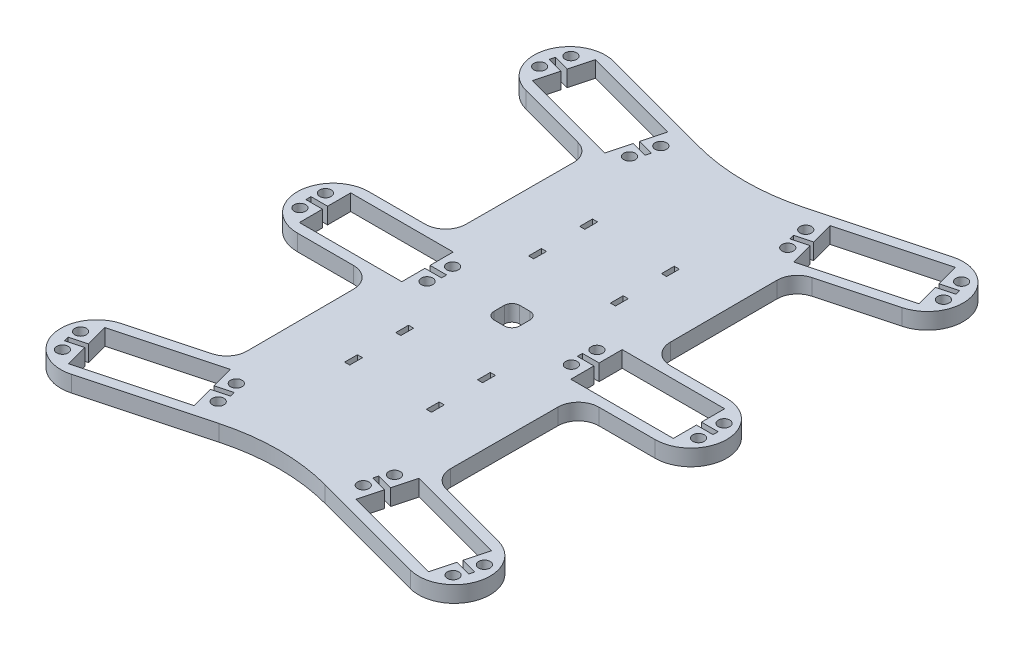
SolidWorks part; units mm, degrees
ref_plane "Front Plane" through (0, 0, 0) normal (0, 0, 1) x (1, 0, 0)
ref_plane "Top Plane" through (0, 0, 0) normal (0, 1, 0) x (1, 0, 0)
ref_plane "Right Plane" through (0, 0, 0) normal (1, 0, 0) x (0, 0, -1)
sketch "Sketch1" plane through (0, 0, 0) normal (0, 1, 0) x (1, 0, 0)
  line L0 (0, 32.1883) -> (0, -21.4181) construction
  line L1 (0, 0) -> (27.1703, 0) construction
  line L2 (-70, 14) -> (-40, 14)
  line L3 (-40, 14) -> (-39.8161, 70)
  line L4 (-39.8161, 70) -> (-73.6235, 79.0587)
  line L5 (-66.3765, 106.1046) -> (0, 88.3191)
  line L10 (-66.3765, 106.1046) -> (-73.6235, 79.0587) construction
  line L12 (-70, 14) -> (-70, -14) construction
  line L14 (-66.3765, -106.1046) -> (0, -88.3191)
  line L15 (-39.8161, -70) -> (-73.6235, -79.0587)
  line L16 (-40, -14) -> (-39.8161, -70)
  line L17 (-70, -14) -> (-40, -14)
  line L18 (66.3765, -106.1046) -> (0, -88.3191)
  line L19 (66.3765, 106.1046) -> (0, 88.3191)
  line L20 (70, 14) -> (70, -14) construction
  line L21 (66.3765, 106.1046) -> (73.6235, 79.0587) construction
  line L22 (70, -14) -> (40, -14)
  line L23 (40, -14) -> (39.8161, -70)
  line L24 (39.8161, -70) -> (73.6235, -79.0587)
  line L25 (39.8161, 70) -> (73.6235, 79.0587)
  line L26 (40, 14) -> (39.8161, 70)
  line L27 (70, 14) -> (40, 14)
  line L28 (-70.4609, 103.1096) -> (-75.6631, 83.6945)
  line L29 (-75.6631, 83.6945) -> (-36.9295, 73.3159)
  line L30 (-36.9295, 73.3159) -> (-31.7272, 92.731)
  line L31 (-31.7272, 92.731) -> (-70.4609, 103.1096)
  line L32 (-51.094, 97.9203) -> (-56.2963, 78.5052) construction
  line L33 (-70, 92.5816) -> (-73.062, 93.4021) construction
  line L34 (-53.12, 10.05) -> (-53.12, -10.05) construction
  line L35 (-73.17, 10.05) -> (-33.07, 10.05)
  line L36 (-73.17, 10.05) -> (-73.17, -10.05)
  line L37 (-73.17, -10.05) -> (-33.07, -10.05)
  line L38 (-33.07, 10.05) -> (-33.07, -10.05)
  line L39 (-73.17, 10.05) -> (-33.07, -10.05) construction
  line L40 (-73.17, -10.05) -> (-33.07, 10.05) construction
  line L41 (-36.9295, -73.3159) -> (-31.7272, -92.731)
  line L42 (-31.7272, -92.731) -> (-70.4609, -103.1096)
  line L43 (-70.4609, -103.1096) -> (-75.6631, -83.6945)
  line L44 (-75.6631, -83.6945) -> (-36.9295, -73.3159)
  line L45 (36.9295, 73.3159) -> (31.7272, 92.731)
  line L46 (75.6631, 83.6945) -> (36.9295, 73.3159)
  line L47 (70.4609, 103.1096) -> (75.6631, 83.6945)
  line L48 (31.7272, 92.731) -> (70.4609, 103.1096)
  line L49 (73.17, -10.05) -> (33.07, 10.05) construction
  line L50 (73.17, 10.05) -> (33.07, -10.05) construction
  line L51 (53.12, 10.05) -> (53.12, -10.05) construction
  line L52 (33.07, 10.05) -> (33.07, -10.05)
  line L53 (73.17, -10.05) -> (33.07, -10.05)
  line L54 (73.17, 10.05) -> (73.17, -10.05)
  line L55 (73.17, 10.05) -> (33.07, 10.05)
  line L56 (36.9295, -73.3159) -> (31.7272, -92.731)
  line L57 (75.6631, -83.6945) -> (36.9295, -73.3159)
  line L58 (31.7272, -92.731) -> (70.4609, -103.1096)
  line L59 (70.4609, -103.1096) -> (75.6631, -83.6945)
  line L60 (-76.4333, 99.4818) -> (-79.0215, 89.8226) construction
  line L61 (-77.7274, 94.6522) -> (-70, 92.5816) construction
  line L62 (-78, 5) -> (-78, -5) construction
  arc A0 (-70, 14) -> (-70, -14) centre (-70, 0) ccw
  arc A1 (-66.3765, 106.1046) -> (-73.6235, 79.0587) centre (-70, 92.5816) ccw
  circle A8 centre (-76.4333, 99.4818) radius 2.25
  circle A9 centre (-79.0215, 89.8226) radius 2.25
  circle A10 centre (-78, 5) radius 2.25
  arc A11 (-66.3765, -106.1046) -> (-73.6235, -79.0587) centre (-70, -92.5816) cw
  circle A12 centre (-79.0215, -89.8226) radius 2.25
  circle A13 centre (-76.4333, -99.4818) radius 2.25
  circle A14 centre (-78, -5) radius 2.25
  circle A15 centre (78, -5) radius 2.25
  circle A16 centre (76.4333, -99.4818) radius 2.25
  circle A17 centre (79.0215, -89.8226) radius 2.25
  arc A18 (66.3765, -106.1046) -> (73.6235, -79.0587) centre (70, -92.5816) ccw
  circle A19 centre (78, 5) radius 2.25
  circle A20 centre (79.0215, 89.8226) radius 2.25
  circle A21 centre (76.4333, 99.4818) radius 2.25
  arc A22 (66.3765, 106.1046) -> (73.6235, 79.0587) centre (70, 92.5816) cw
  arc A23 (70, 14) -> (70, -14) centre (70, 0) cw
  circle A24 centre (-30.957, 76.9437) radius 2.25
  circle A25 centre (-28.3688, 86.603) radius 2.25
  circle A26 centre (-28.24, -5) radius 2.25
  circle A27 centre (-28.24, 5) radius 2.25
  circle A28 centre (-28.3688, -86.603) radius 2.25
  circle A29 centre (-30.957, -76.9437) radius 2.25
  circle A30 centre (28.3688, 86.603) radius 2.25
  circle A31 centre (30.957, 76.9437) radius 2.25
  circle A32 centre (28.24, 5) radius 2.25
  circle A33 centre (28.24, -5) radius 2.25
  circle A34 centre (30.957, -76.9437) radius 2.25
  circle A35 centre (28.3688, -86.603) radius 2.25
  point P60 (-51.094, 97.9203)
  point P62 (-56.2963, 78.5052)
  point P65 (-73.062, 93.4021)
  point P71 (-53.12, 0)
  point P108 (53.12, 0)
  point P118 (-83.523, 96.2051)
  dimension "D2" = 14
  dimension "D3" = 10
  dimension "D8" = 4.5
  dimension "D1" = 75
  dimension "D4" = 70
  dimension "D5" = 30
  dimension "D6" = 35
  dimension "D7" = 56
  dimension "D9" = 8
  dimension "D10" = 5
  dimension "D11" = 10
  dimension "D12" = 40.1
  dimension "D13" = 20.1
  dimension "D14" = 4.83
  dimension "D15" = 40.1
  dimension "D16" = 20.1
  dimension "D17" = 4.83
  dimension "D18" = 8
extrude "Boss-Extrude1" add sketch "Sketch1" along normal blind 6.35
fillet "Fillet1" radius 80 2 edges at (0, 3.175, -88.3191) (0, 3.175, 88.3191)
fillet "Fillet2" radius 8 8 edges at (39.8161, 3.175, 70) (40, 3.175, 14) (40, 3.175, -14) (39.8161, 3.175, -70) (-39.8161, 3.175, -70) (-40, 3.175, -14) (-40, 3.175, 14) (-39.8161, 3.175, 70)
sketch "Sketch5" plane through (0, 6.35, 0) normal (0, 1, 0) x (1, 0, 0)
  line L0 (0, 91.1411) -> (0, -91.1411) construction
  line L1 (-84, 0) -> (84, 0) construction
  line L2 (-33.07, -10.05) -> (-33.07, 10.05) construction
  line L3 (-33.07, 1) -> (-26.57, 1)
  line L4 (-33.07, 1) -> (-33.07, -1)
  line L5 (-33.07, -1) -> (-26.57, -1)
  line L6 (-26.57, 1) -> (-26.57, -1)
  line L7 (-33.07, 1) -> (-26.57, -1) construction
  line L8 (-33.07, -1) -> (-26.57, 1) construction
  line L9 (-33.07, 10.05) -> (-73.17, 10.05) construction
  line L10 (-53.12, 10.05) -> (-53.12, -10.05) construction
  line L11 (-73.17, -10.05) -> (-33.07, -10.05) construction
  line L12 (-73.17, -1) -> (-79.67, 1) construction
  line L13 (-73.17, 1) -> (-79.67, -1) construction
  line L14 (-79.67, 1) -> (-79.67, -1)
  line L15 (-73.17, -1) -> (-79.67, -1)
  line L16 (-73.17, 1) -> (-73.17, -1)
  line L17 (-73.17, 1) -> (-79.67, 1)
  line L18 (-34.0695, 83.9894) -> (-27.791, 82.307)
  line L19 (-36.9295, 73.3159) -> (-31.7272, 92.731) construction
  line L20 (-27.791, 82.307) -> (-28.3087, 80.3752)
  line L21 (-28.3087, 80.3752) -> (-34.5872, 82.0575)
  line L22 (-34.0695, 83.9894) -> (-34.5872, 82.0575)
  line L23 (-51.094, 97.9203) -> (-56.2963, 78.5052) construction
  line L24 (-31.7272, 92.731) -> (-70.4609, 103.1096) construction
  line L25 (-75.6631, 83.6945) -> (-36.9295, 73.3159) construction
  line L26 (-72.8032, 94.368) -> (-73.3208, 92.4362)
  line L27 (-79.5993, 94.1185) -> (-73.3208, 92.4362)
  line L28 (-79.0817, 96.0503) -> (-79.5993, 94.1185)
  line L29 (-72.8032, 94.368) -> (-79.0817, 96.0503)
  line L30 (51.094, 97.9203) -> (56.2963, 78.5052) construction
  line L31 (72.8032, 94.368) -> (79.0817, 96.0503)
  line L32 (79.0817, 96.0503) -> (79.5993, 94.1185)
  line L33 (79.5993, 94.1185) -> (73.3208, 92.4362)
  line L34 (72.8032, 94.368) -> (73.3208, 92.4362)
  line L35 (34.0695, 83.9894) -> (34.5872, 82.0575)
  line L36 (28.3087, 80.3752) -> (34.5872, 82.0575)
  line L37 (27.791, 82.307) -> (28.3087, 80.3752)
  line L38 (34.0695, 83.9894) -> (27.791, 82.307)
  line L39 (73.17, 1) -> (79.67, -1) construction
  line L40 (73.17, -1) -> (79.67, 1) construction
  line L41 (53.12, 10.05) -> (53.12, -10.05) construction
  line L42 (33.07, -1) -> (26.57, 1) construction
  line L43 (33.07, 1) -> (26.57, -1) construction
  line L44 (73.17, 1) -> (79.67, 1)
  line L45 (73.17, 1) -> (73.17, -1)
  line L46 (73.17, -1) -> (79.67, -1)
  line L47 (79.67, 1) -> (79.67, -1)
  line L48 (26.57, 1) -> (26.57, -1)
  line L49 (33.07, -1) -> (26.57, -1)
  line L50 (33.07, 1) -> (33.07, -1)
  line L51 (33.07, 1) -> (26.57, 1)
  line L52 (51.094, -97.9203) -> (56.2963, -78.5052) construction
  line L53 (-51.094, -97.9203) -> (-56.2963, -78.5052) construction
  line L54 (34.0695, -83.9894) -> (27.791, -82.307)
  line L55 (27.791, -82.307) -> (28.3087, -80.3752)
  line L56 (28.3087, -80.3752) -> (34.5872, -82.0575)
  line L57 (34.0695, -83.9894) -> (34.5872, -82.0575)
  line L58 (72.8032, -94.368) -> (73.3208, -92.4362)
  line L59 (79.5993, -94.1185) -> (73.3208, -92.4362)
  line L60 (79.0817, -96.0503) -> (79.5993, -94.1185)
  line L61 (72.8032, -94.368) -> (79.0817, -96.0503)
  line L62 (-72.8032, -94.368) -> (-79.0817, -96.0503)
  line L63 (-79.0817, -96.0503) -> (-79.5993, -94.1185)
  line L64 (-79.5993, -94.1185) -> (-73.3208, -92.4362)
  line L65 (-72.8032, -94.368) -> (-73.3208, -92.4362)
  line L66 (-34.0695, -83.9894) -> (-34.5872, -82.0575)
  line L67 (-28.3087, -80.3752) -> (-34.5872, -82.0575)
  line L68 (-27.791, -82.307) -> (-28.3087, -80.3752)
  line L69 (-34.0695, -83.9894) -> (-27.791, -82.307)
  arc A0 (-20.7055, 93.8671) -> (20.7055, 93.8671) centre (0, 171.1411) ccw construction
  arc A1 (20.7055, -93.8671) -> (-20.7055, -93.8671) centre (0, -171.1411) ccw construction
  arc A2 (-70, 14) -> (-70, -14) centre (-70, 0) ccw construction
  arc A3 (70, -14) -> (70, 14) centre (70, 0) ccw construction
  point P16 (-29.82, 0)
  point P23 (-53.12, 10.05)
  point P34 (-76.42, 0)
  point P39 (-34.3284, 83.0234)
  point P42 (-34.3284, 83.0234)
  point P53 (-73.062, 93.4021)
  point P64 (73.062, 93.4021)
  point P65 (34.3284, 83.0234)
  point P76 (76.42, 0)
  point P77 (29.82, 0)
  point P98 (34.3284, -83.0234)
  point P99 (73.062, -93.4021)
  point P100 (-73.062, -93.4021)
  point P101 (-34.3284, -83.0234)
  dimension "D1" = 2
  dimension "D2" = 6.5
  dimension "D3" = 2
  dimension "D4" = 6.5
extrude "Cut-Extrude2" cut sketch "Sketch5" against normal through all
sketch "Sketch6" plane through (0, 6.35, 0) normal (0, 1, 0) x (1, 0, 0)
  line L0 (-84, 0) -> (84, 0) construction
  line L1 (0, -91.1411) -> (0, 91.1411) construction
  line L2 (17, -48.5) -> (15, -43.5) construction
  line L3 (-17, -23.5) -> (-15, -23.5)
  line L4 (-17, -23.5) -> (-17, -28.5)
  line L5 (-17, -28.5) -> (-15, -28.5)
  line L6 (-15, -23.5) -> (-15, -28.5)
  line L7 (-17, -23.5) -> (-15, -28.5) construction
  line L8 (-17, -28.5) -> (-15, -23.5) construction
  line L9 (-17, -43.5) -> (-15, -43.5)
  line L10 (-17, -43.5) -> (-17, -48.5)
  line L11 (-17, -48.5) -> (-15, -48.5)
  line L12 (-15, -43.5) -> (-15, -48.5)
  line L13 (-17, -43.5) -> (-15, -48.5) construction
  line L14 (-17, -48.5) -> (-15, -43.5) construction
  line L15 (17, -43.5) -> (15, -48.5) construction
  line L16 (17, -28.5) -> (15, -23.5) construction
  line L17 (17, -23.5) -> (15, -28.5) construction
  line L18 (15, -43.5) -> (15, -48.5)
  line L19 (17, -48.5) -> (15, -48.5)
  line L20 (17, -43.5) -> (17, -48.5)
  line L21 (17, -43.5) -> (15, -43.5)
  line L22 (15, -23.5) -> (15, -28.5)
  line L23 (17, -28.5) -> (15, -28.5)
  line L24 (17, -23.5) -> (17, -28.5)
  line L25 (17, -23.5) -> (15, -23.5)
  line L26 (17, 23.5) -> (15, 28.5) construction
  line L27 (17, 28.5) -> (15, 23.5) construction
  line L28 (17, 43.5) -> (15, 48.5) construction
  line L29 (-17, 48.5) -> (-15, 43.5) construction
  line L30 (-17, 43.5) -> (-15, 48.5) construction
  line L31 (-17, 28.5) -> (-15, 23.5) construction
  line L32 (-17, 23.5) -> (-15, 28.5) construction
  line L33 (17, 48.5) -> (15, 43.5) construction
  line L34 (17, 23.5) -> (15, 23.5)
  line L35 (17, 23.5) -> (17, 28.5)
  line L36 (17, 28.5) -> (15, 28.5)
  line L37 (15, 23.5) -> (15, 28.5)
  line L38 (17, 43.5) -> (15, 43.5)
  line L39 (17, 43.5) -> (17, 48.5)
  line L40 (17, 48.5) -> (15, 48.5)
  line L41 (15, 43.5) -> (15, 48.5)
  line L42 (-15, 43.5) -> (-15, 48.5)
  line L43 (-17, 48.5) -> (-15, 48.5)
  line L44 (-17, 43.5) -> (-17, 48.5)
  line L45 (-17, 43.5) -> (-15, 43.5)
  line L46 (-15, 23.5) -> (-15, 28.5)
  line L47 (-17, 28.5) -> (-15, 28.5)
  line L48 (-17, 23.5) -> (-17, 28.5)
  line L49 (-17, 23.5) -> (-15, 23.5)
  line L51 (-5, 5) -> (5, 5)
  line L52 (-5, 5) -> (-5, -5)
  line L53 (-5, -5) -> (5, -5)
  line L54 (5, 5) -> (5, -5)
  line L55 (-5, 5) -> (5, -5) construction
  line L56 (-5, -5) -> (5, 5) construction
  arc A0 (-70, 14) -> (-70, -14) centre (-70, 0) ccw construction
  arc A1 (70, -14) -> (70, 14) centre (70, 0) ccw construction
  arc A2 (20.7055, -93.8671) -> (-20.7055, -93.8671) centre (0, -171.1411) ccw construction
  arc A3 (-20.7055, 93.8671) -> (20.7055, 93.8671) centre (0, 171.1411) ccw construction
  point P16 (-16, -26)
  point P21 (-16, -46)
  point P34 (16, -46)
  point P35 (16, -26)
  point P52 (16, 26)
  point P53 (16, 46)
  point P54 (-16, 46)
  point P55 (-16, 26)
  point P56 (0, 0)
  dimension "D1" = 16
  dimension "D2" = 5
  dimension "D3" = 2
  dimension "D4" = 20
  dimension "D5" = 26
  dimension "D6" = 10
  dimension "D7" = 10
extrude "Cut-Extrude3" cut sketch "Sketch6" against normal blind 10
fillet "Fillet3" radius 3 4 edges at (-5, 3.175, 5) (5, 3.175, 5) (-5, 3.175, -5) (5, 3.175, -5)
